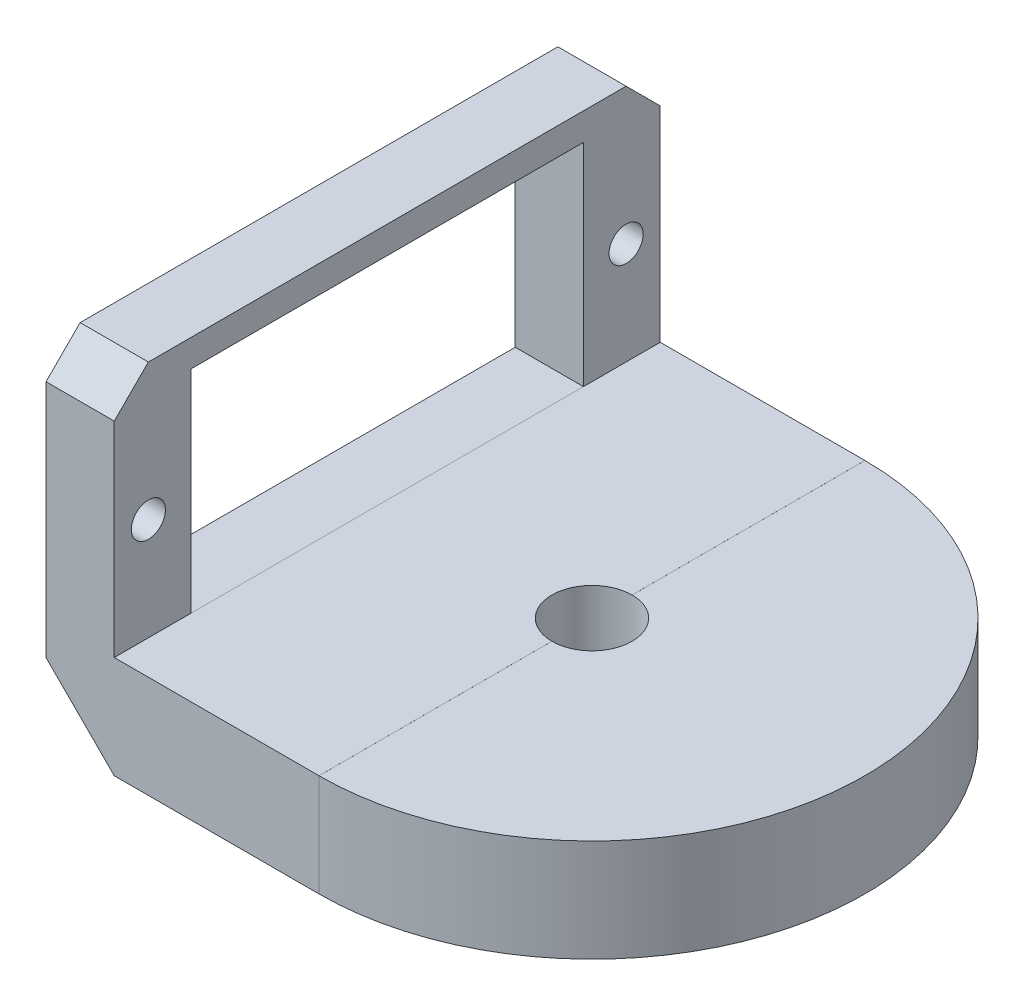
SolidWorks part; units mm, degrees
ref_plane "前视基准面" through (0, 0, 0) normal (0, 0, 1) x (1, 0, 0)
ref_plane "上视基准面" through (0, 0, 0) normal (0, 1, 0) x (1, 0, 0)
ref_plane "右视基准面" through (0, 0, 0) normal (1, 0, 0) x (0, 0, -1)
other "Configuration Table"
sketch "Sketch1" plane through (0, 0, 0) normal (1, 0, 0) x (0, 0, -1)
  line L1 (0, 0) -> (32, 0)
  line L2 (0, 0) -> (0, 16)
  line L3 (0, 16) -> (32, 16)
  line L4 (32, 0) -> (32, 16)
  line L5 (4.5, 1.6) -> (27.5, 1.6)
  line L6 (4.5, 1.6) -> (4.5, 14.4)
  line L7 (4.5, 14.4) -> (27.5, 14.4)
  line L8 (27.5, 1.6) -> (27.5, 14.4)
  dimension "D1" = 16
  dimension "D2" = 32
  dimension "D3" = 1.6
  dimension "D4" = 1.6
  dimension "D5" = 23
  dimension "D6" = 4.5
extrude "Boss-Extrude1" add sketch "Sketch1" along normal blind 4
sketch "Sketch3" plane through (4, 0, 0) normal (1, 0, 0) x (0, 0, -1)
  line L5 (0, 16) -> (0, 0) construction
  line L6 (32, 0) -> (0, 0)
  line L7 (32, 0) -> (32, 2.0013)
  line L8 (32, 2.0013) -> (0, 2.0013)
  line L9 (0, 0) -> (0, 2.0013)
extrude "Boss-Extrude3" add sketch "Sketch3" along normal blind 12
sketch "Sketch7" plane through (0, 0, 0) normal (0, -1, 0) x (1, 0, 0)
  line L0 (0, -32) -> (0, 0) construction
  line L3 (0, 0) -> (16, 0)
  line L4 (0, 0) -> (0, -32)
  line L5 (0, -32) -> (16, -32)
  arc A0 (16, -32) -> (16, 0) centre (16, -16) ccw
extrude "Boss-Extrude5" add sketch "Sketch7" along normal blind 4 and the other way blind 2
chamfer "Chamfer1" distance 4 angle 45 1 edges at (0, -4, -16)
sketch "Sketch8" plane through (0, -4, 0) normal (0, -1, 0) x (1, 0, 0)
  circle A0 centre (16, -16) radius 2.35
  dimension "D1" = 4.7
extrude "Cut-Extrude2" cut sketch "Sketch8" against normal through all
sketch "Sketch9" plane through (0, 0, 0) normal (-1, 0, 0) x (0, 0, 1)
  line L0 (-27.5, 8) -> (-32, 8) construction
  line L2 (-32, 0) -> (-32, 16) construction
  line L3 (-32, 8) -> (-30, 8) construction
  line L4 (-4.5, 8) -> (0, 8) construction
  line L6 (0, 16) -> (0, 0) construction
  line L7 (0, 8) -> (-2, 8) construction
  circle A0 centre (-30, 8) radius 1
  circle A1 centre (-2, 8) radius 1
  point P16 (0, 0)
  dimension "D3" = 2
  dimension "D4" = 2
  dimension "D1" = 2
  dimension "D2" = 2
extrude "Cut-Extrude3" cut sketch "Sketch9" against normal through all
chamfer "Chamfer2" distance 2 angle 45 2 edges at (2, 16, 0) (2, 16, -32)
